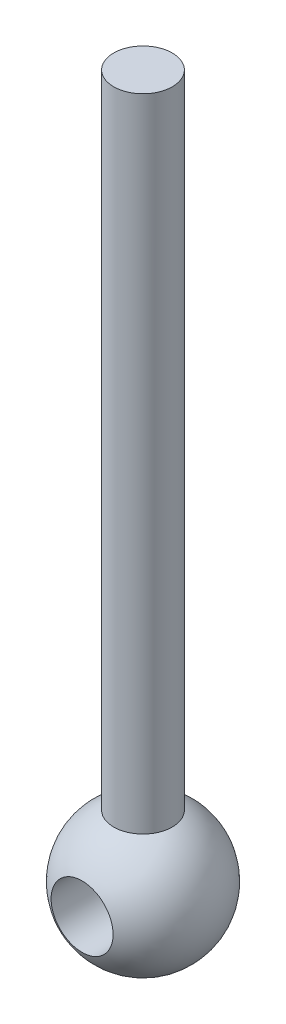
SolidWorks part; units mm, degrees
material "Plain Carbon Steel"
ref_plane "Front Plane" through (0, 0, 0) normal (0, 0, 1) x (1, 0, 0)
ref_plane "Top Plane" through (0, 0, 0) normal (0, 1, 0) x (1, 0, 0)
ref_plane "Right Plane" through (0, 0, 0) normal (1, 0, 0) x (0, 0, -1)
sketch "Sketch1" plane through (0, 0, 0) normal (0, 1, 0) x (1, 0, 0)
  line L0 (0, -6.2385) -> (0, 6.2385) construction
  line L1 (3.175, 6.2385) -> (3.175, -6.2385)
  arc A0 (3.175, -6.2385) -> (3.175, 6.2385) centre (0, 0) ccw
revolve "Revolve1" add sketch "Sketch1" angle 360 about L0
sketch "Sketch2" plane through (0, 0, 0) normal (0, 1, 0) x (1, 0, 0)
  circle A0 centre (0, 0) radius 3
  dimension "D1" = 6
extrude "Boss-Extrude1" add sketch "Sketch2" along normal blind 68.5 from offset 3.5
